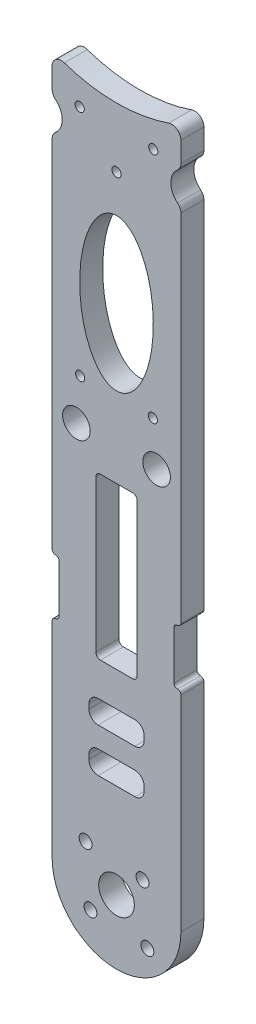
SolidWorks part; units mm, degrees
ref_plane "Front Plane" through (0, 0, 0) normal (0, 0, 1) x (1, 0, 0)
ref_plane "Top Plane" through (0, 0, 0) normal (0, 1, 0) x (1, 0, 0)
ref_plane "Right Plane" through (0, 0, 0) normal (1, 0, 0) x (0, 0, -1)
sketch "Sketch1" plane through (0, 0, 0) normal (0, 0, 1) x (1, 0, 0)
  line L0 (-14, 0) -> (-14, 44.6414)
  line L1 (0, 149.0732) -> (0, -14) construction
  line L2 (14, 0) -> (14, 44.6414)
  line L3 (-14, 0) -> (14, 0) construction
  line L4 (-6.7175, 6.7175) -> (6.7175, -6.7175) construction
  line L5 (-4, 29.9839) -> (4, 29.9839)
  line L6 (-9.9779, -9.9779) -> (8.2462, 8.2462) construction
  line L7 (-14, 144.6611) -> (-14, 149.0732)
  line L8 (-4, 20.4839) -> (4, 20.4839)
  line L9 (-6, 22.4839) -> (-6, 23.4839)
  line L10 (-4, 25.4839) -> (4, 25.4839)
  line L11 (6, 22.4839) -> (6, 23.4839)
  line L12 (-6, 20.4839) -> (6, 25.4839) construction
  line L13 (-6, 25.4839) -> (6, 20.4839) construction
  line L14 (14, 144.6611) -> (14, 149.0732)
  line L15 (-6, 31.9839) -> (-6, 32.9839)
  line L16 (-4, 34.9839) -> (4, 34.9839)
  line L17 (6, 31.9839) -> (6, 32.9839)
  line L18 (-6, 29.9839) -> (6, 34.9839) construction
  line L19 (-6, 34.9839) -> (6, 29.9839) construction
  line L21 (-3.5, 42.4439) -> (3.5, 42.4439)
  line L22 (-4.5, 43.4439) -> (-4.5, 76.4439)
  line L23 (-3.5, 77.4439) -> (3.5, 77.4439)
  line L24 (4.5, 43.4439) -> (4.5, 76.4439)
  line L25 (-4.5, 42.4439) -> (4.5, 77.4439) construction
  line L26 (-4.5, 77.4439) -> (4.5, 42.4439) construction
  line L27 (-4, 51.3814) -> (0, 51.3814) construction
  line L28 (-13.26, 57.3814) -> (-13.24, 57.3814)
  line L29 (-12.5, 56.6414) -> (-12.5, 46.1214)
  line L30 (-13.26, 45.3814) -> (-13.24, 45.3814)
  line L31 (13.26, 45.3814) -> (13.24, 45.3814)
  line L32 (12.5, 56.6414) -> (12.5, 46.1214)
  line L33 (13.26, 57.3814) -> (13.24, 57.3814)
  line L34 (14, 58.1214) -> (14, 135.3474)
  line L35 (-14, 58.1214) -> (-14, 135.3474)
  arc A0 (-14, 0) -> (14, 0) centre (0, 0) ccw
  arc A1 (-11.3514, 150.9651) -> (11.3514, 150.9651) centre (0, 184.0732) ccw
  circle A2 centre (-8, 144.3712) radius 1
  circle A3 centre (6.7175, -6.7175) radius 1.4
  circle A4 centre (-5.6569, -5.6569) radius 1.4
  circle A5 centre (5.6569, 5.6569) radius 1.4
  circle A6 centre (-6.7175, 6.7175) radius 1.4
  circle A7 centre (8, 144.3712) radius 1
  circle A8 centre (0, 136.0732) radius 1
  circle A9 centre (0, 136.0732) radius 1 construction
  circle A10 centre (-8, 144.3712) radius 1 construction
  circle A11 centre (8, 144.3712) radius 1 construction
  circle A12 centre (7.9033, 93.7383) radius 1
  circle A13 centre (0, 184.0732) radius 35 construction
  arc A14 (6, 31.9839) -> (4, 29.9839) centre (4, 31.9839) cw
  arc A15 (4, 34.9839) -> (6, 32.9839) centre (4, 32.9839) cw
  circle A16 centre (7.9033, 93.7383) radius 1 construction
  arc A17 (-4, 34.9839) -> (-6, 32.9839) centre (-4, 32.9839) ccw
  arc A18 (-6, 31.9839) -> (-4, 29.9839) centre (-4, 31.9839) ccw
  arc A19 (4.5, 43.4439) -> (3.5, 42.4439) centre (3.5, 43.4439) cw
  circle A20 centre (8.7156, 84.4537) radius 3
  circle A21 centre (8.7156, 84.4537) radius 1.45 construction
  arc A22 (6, 22.4839) -> (4, 20.4839) centre (4, 22.4839) cw
  arc A23 (4, 25.4839) -> (6, 23.4839) centre (4, 23.4839) cw
  arc A24 (-4, 25.4839) -> (-6, 23.4839) centre (-4, 23.4839) ccw
  arc A25 (-6, 22.4839) -> (-4, 20.4839) centre (-4, 22.4839) ccw
  arc A26 (-14, 149.0732) -> (-11.3514, 150.9651) centre (-12, 149.0732) cw
  arc A27 (11.3514, 150.9651) -> (14, 149.0732) centre (12, 149.0732) cw
  arc A28 (-13.2731, 143.1186) -> (-13.2731, 136.8899) centre (-15.8435, 140.0042) cw
  arc A29 (13.2731, 143.1186) -> (13.2731, 136.8899) centre (15.8435, 140.0042) ccw
  arc A30 (14, 135.3474) -> (13.2731, 136.8899) centre (12, 135.3474) ccw
  arc A31 (13.2731, 143.1186) -> (14, 144.6611) centre (12, 144.6611) ccw
  arc A32 (-14, 144.6611) -> (-13.2731, 143.1186) centre (-12, 144.6611) ccw
  arc A33 (-13.2731, 136.8899) -> (-14, 135.3474) centre (-12, 135.3474) ccw
  circle A34 centre (-7.9033, 93.7383) radius 1
  circle A35 centre (-8.7156, 84.4537) radius 3
  arc A36 (-3.5, 42.4439) -> (-4.5, 43.4439) centre (-3.5, 43.4439) cw
  arc A37 (-4.5, 76.4439) -> (-3.5, 77.4439) centre (-3.5, 76.4439) cw
  arc A38 (3.5, 77.4439) -> (4.5, 76.4439) centre (3.5, 76.4439) cw
  arc A39 (-14, 44.6414) -> (-13.26, 45.3814) centre (-13.26, 44.6414) cw
  arc A40 (-13.24, 45.3814) -> (-12.5, 46.1214) centre (-13.24, 46.1214) ccw
  arc A41 (-12.5, 56.6414) -> (-13.24, 57.3814) centre (-13.24, 56.6414) ccw
  arc A42 (-13.26, 57.3814) -> (-14, 58.1214) centre (-13.26, 58.1214) cw
  arc A43 (12.5, 46.1214) -> (13.24, 45.3814) centre (13.24, 46.1214) ccw
  arc A44 (13.26, 45.3814) -> (14, 44.6414) centre (13.26, 44.6414) cw
  arc A45 (13.24, 57.3814) -> (12.5, 56.6414) centre (13.24, 56.6414) ccw
  arc A46 (13.26, 57.3814) -> (14, 58.1214) centre (13.26, 58.1214) ccw
  ellipse E1 centre (0, 111.3839) end of major axis (0, 127.8839) minor radius 8
  point P33 (0, 32.4839)
  point P43 (0, 22.9839)
  point P82 (-14, 151.9952)
  point P85 (14, 151.9952)
  point P94 (14, 136.4115)
  point P97 (14, 143.597)
  point P100 (-14, 143.597)
  point P103 (-14, 136.4115)
  point P109 (0, 59.9439)
  point P135 (-12.5, 51.3814)
  point P141 (-14, 45.3814)
  point P144 (-12.5, 45.3814)
  point P147 (-12.5, 57.3814)
  point P150 (-14, 57.3814)
  point P153 (12.5, 45.3814)
  point P156 (14, 45.3814)
  point P159 (12.5, 57.3814)
  point P162 (14, 57.3814)
  dimension "D3" = 14
  dimension "D5" = 2
  dimension "D2" = 2
  dimension "D4" = 12
  dimension "D8" = 35
  dimension "D10" = 9
  dimension "D11" = 9.5
  dimension "D7" = 2
  dimension "D15" = 2
  dimension "D16" = 2
  dimension "D18" = 2.8
  dimension "D19" = 9.5
  dimension "D20" = 8
  dimension "D14" = 1
  dimension "D24" = 0.74
  dimension "D6" = 5
  dimension "D9" = 4.5
  dimension "D12" = 35
  dimension "D13" = 8
  dimension "D17" = 8
  dimension "D21" = 1.5
  dimension "D22" = 163.0732
  dimension "D23" = 6
extrude "Boss-Extrude1" add sketch "Sketch1" along normal blind 5
sketch "Sketch2" plane through (0, 0, 5) normal (0, 0, 1) x (1, 0, 0)
  circle A0 centre (0, 0) radius 3.875
extrude "Cut-Extrude1" cut sketch "Sketch2" against normal up to next
